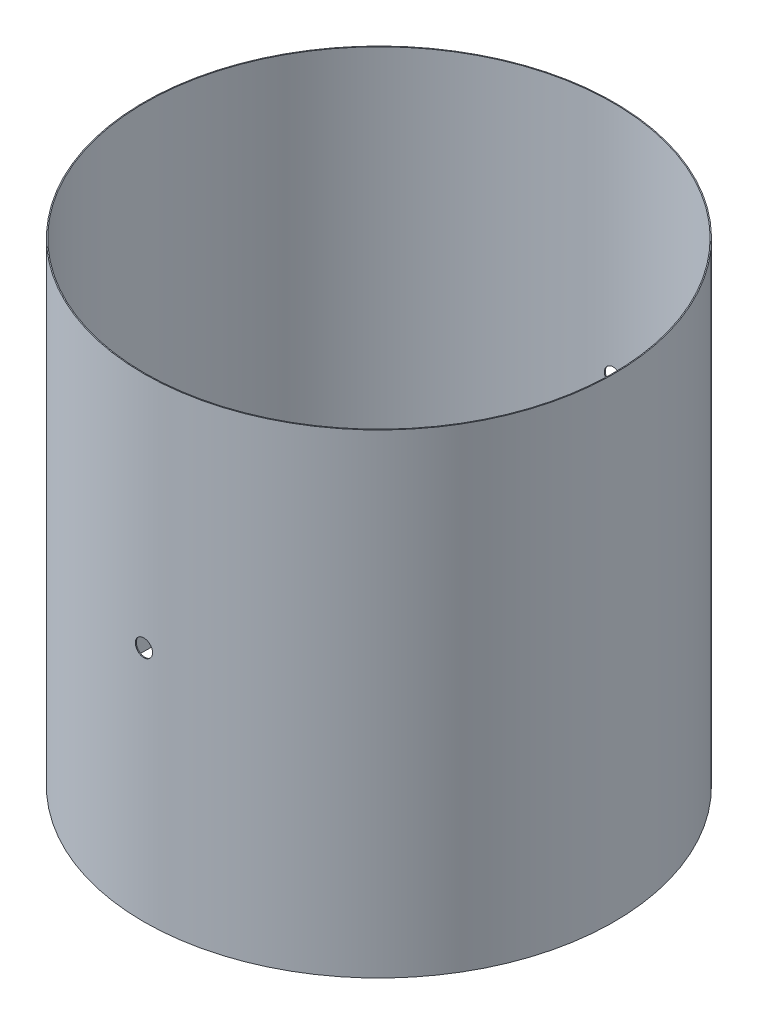
SolidWorks part; units mm, degrees
material "Galvanized Steel"
ref_plane "Front Plane" through (0, 0, 0) normal (0, 0, 1) x (1, 0, 0)
ref_plane "Top Plane" through (0, 0, 0) normal (0, 1, 0) x (1, 0, 0)
ref_plane "Right Plane" through (0, 0, 0) normal (1, 0, 0) x (0, 0, -1)
sketch "Sketch1" plane through (0, 0, 0) normal (0, 1, 0) x (1, 0, 0)
  circle A0 centre (0, 0) radius 376.5
  circle A1 centre (0, 0) radius 375
  dimension "D1" = 750
  dimension "763" = 753
extrude "Boss-Extrude1" add sketch "Sketch1" along normal mid plane 760
sketch "Sketch2" plane through (0, 0, 0) normal (0, 0, 1) x (1, 0, 0)
  line L0 (-376.5, -380) -> (376.5, -380) construction
  circle A0 centre (0, 0) radius 13.75
  dimension "D1" = 27.5
  dimension "D2" = 380
extrude "Cut-Extrude1" cut sketch "Sketch2" against normal through all both and the other way through all
